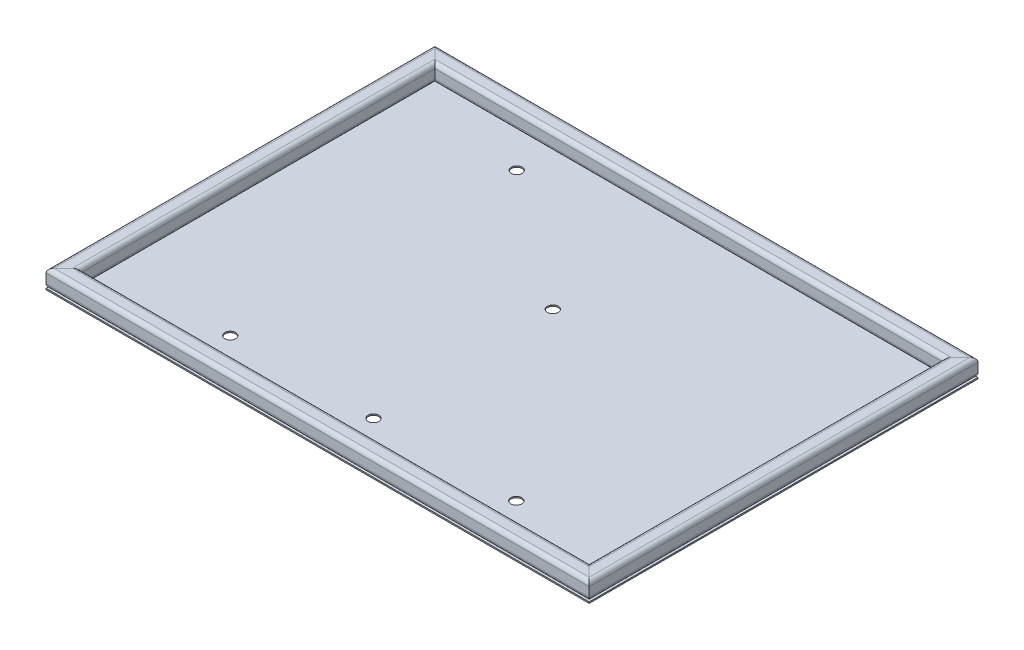
SolidWorks part; units mm, degrees
ref_plane "Alzado" through (0, 0, 0) normal (0, 0, 1) x (1, 0, 0)
ref_plane "Planta" through (0, 0, 0) normal (0, 1, 0) x (1, 0, 0)
ref_plane "Vista lateral" through (0, 0, 0) normal (1, 0, 0) x (0, 0, -1)
sketch "Croquis1" plane through (0, 0, 0) normal (0, 1, 0) x (1, 0, 0)
  line L1 (-398.2, 285) -> (398.2, 285)
  line L2 (-398.2, 285) -> (-398.2, -285)
  line L3 (-398.2, -285) -> (398.2, -285)
  line L4 (398.2, 285) -> (398.2, -285)
  line L5 (-398.2, 285) -> (398.2, -285) construction
  line L6 (-398.2, -285) -> (398.2, 285) construction
  point P0 (0, 0)
  dimension "D1" = 570
  dimension "D2" = 796.4
other "Tubo cuadrado 2 X 2 X 0.25(1)"
ref_plane "Plano1" through (-385.5, 12.7, -285) normal (0, 0, 1) x (1, 0, 0)
sketch "Sketch1" plane through (-385.5, 12.7, -285) normal (0, 0, 1) x (1, 0, 0)
  line L0 (-6.7, -9.7) -> (6.7, -9.7)
  line L1 (-9.7, -6.7) -> (-9.7, 6.7)
  line L2 (6.7, 9.7) -> (-6.7, 9.7)
  line L3 (9.7, 6.7) -> (9.7, -6.7)
  line L4 (-6.7, -12.7) -> (6.7, -12.7)
  line L5 (-12.7, -6.7) -> (-12.7, 6.7)
  line L6 (6.7, 12.7) -> (-6.7, 12.7)
  line L7 (12.7, 6.7) -> (12.7, -6.7)
  line L8 (0, 0) -> (9.7, 0) construction
  line L9 (0, 0) -> (0, 9.7) construction
  arc A0 (12.7, 6.7) -> (6.7, 12.7) centre (6.7, 6.7) ccw
  arc A1 (6.7, -12.7) -> (12.7, -6.7) centre (6.7, -6.7) ccw
  arc A2 (-12.7, -6.7) -> (-6.7, -12.7) centre (-6.7, -6.7) ccw
  arc A3 (-6.7, 12.7) -> (-12.7, 6.7) centre (-6.7, 6.7) ccw
  arc A4 (-6.7, 9.7) -> (-9.7, 6.7) centre (-6.7, 6.7) ccw
  arc A5 (9.7, 6.7) -> (6.7, 9.7) centre (6.7, 6.7) ccw
  arc A6 (6.7, -9.7) -> (9.7, -6.7) centre (6.7, -6.7) ccw
  arc A7 (-9.7, -6.7) -> (-6.7, -9.7) centre (-6.7, -6.7) ccw
  point P3 (0, 12.7)
  point P4 (12.7, 0)
  point P5 (0, -12.7)
  point P6 (-12.7, 0)
  point P7 (-12.7, 12.7)
  point P8 (-12.7, -12.7)
  point P33 (0, 0)
  point P35 (12.7, -12.7)
  point P36 (12.7, 12.7)
  point P37 (0, 0)
  dimension "D1" = 6
  dimension "Thickness" = 3
  dimension "V_leg" = 25.4
sketch "Croquis3" plane through (0, 0, 0) normal (0, -1, 0) x (1, 0, 0)
  line L1 (398.2, 285) -> (-398.2, 285)
  line L2 (398.2, 285) -> (398.2, -285)
  line L3 (398.2, -285) -> (-398.2, -285)
  line L4 (-398.2, 285) -> (-398.2, -285)
  line L5 (398.2, 285) -> (-398.2, -285) construction
  line L6 (398.2, -285) -> (-398.2, 285) construction
  point P0 (0, 0)
extrude "Saliente-Extruir1" add sketch "Croquis3" along normal blind 1.9 separate body
ref_plane "Plano2" through (0, 0, 210) normal (0, 0, 1) x (1, 0, 0)
sketch "Croquis4" plane through (0, 0, 0) normal (0, 1, 0) x (1, 0, 0)
  circle A0 centre (216.35, -210) radius 7.9375
  circle A3 centre (6.95, -210) radius 7.9375
  circle A6 centre (-203.05, -210) radius 7.9375
  circle A9 centre (-203.05, 209.995) radius 7.9375
  circle A13 centre (0, 59.858) radius 7.9375
extrude "Cortar-Extruir1" cut sketch "Croquis4" against normal blind 10
